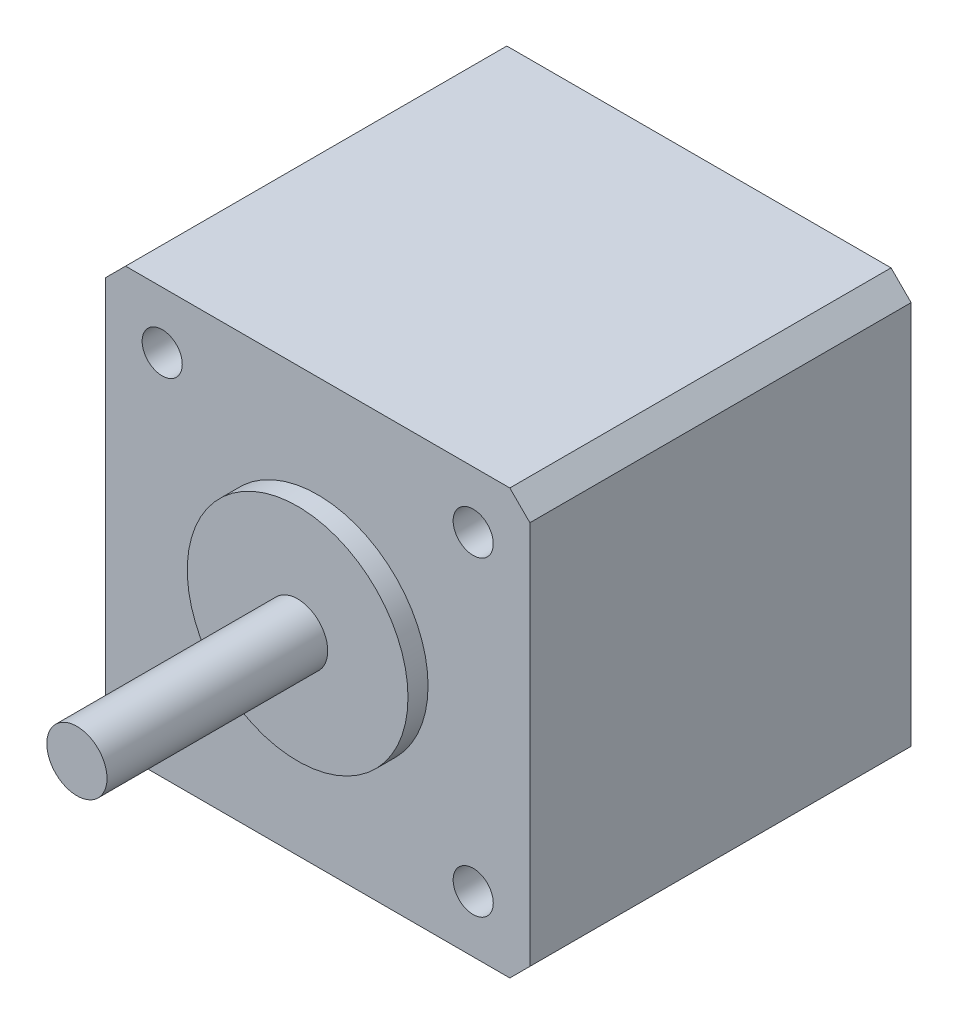
SolidWorks part; units mm, degrees
ref_plane "Plan de face" through (0, 0, 0) normal (0, 0, 1) x (1, 0, 0)
ref_plane "Plan de dessus" through (0, 0, 0) normal (0, 1, 0) x (1, 0, 0)
ref_plane "Plan de droite" through (0, 0, 0) normal (1, 0, 0) x (0, 0, -1)
sketch "Esquisse1" plane through (0, 0, 0) normal (0, 0, 1) x (1, 0, 0)
  line L0 (0, 21.15) -> (0, -21.15) construction
  line L1 (-19.15, -21.15) -> (19.15, -21.15)
  line L2 (-21.15, -19.15) -> (-21.15, 19.15)
  line L3 (-19.15, 21.15) -> (19.15, 21.15)
  line L4 (21.15, -19.15) -> (21.15, 19.15)
  line L5 (-21.15, -21.15) -> (21.15, 21.15) construction
  line L6 (-21.15, 21.15) -> (21.15, -21.15) construction
  line L7 (0, 0) -> (-21.15, 0) construction
  line L8 (-21.15, 19.15) -> (-19.15, 21.15)
  line L9 (21.15, 19.15) -> (19.15, 21.15)
  line L10 (19.15, -21.15) -> (21.15, -19.15)
  line L11 (-19.15, -21.15) -> (-21.15, -19.15)
  circle A0 centre (-15.5, 15.5) radius 2
  circle A1 centre (15.5, 15.5) radius 2
  circle A2 centre (15.5, -15.5) radius 2
  circle A3 centre (-15.5, -15.5) radius 2
  point P0 (0, 0)
  point P12 (15.5, 15.5)
  dimension "D4" = 4
  dimension "D1" = 42.3
  dimension "D2" = 42.3
  dimension "D3" = 15.5
extrude "BASE RECTANGULAIRE" add sketch "Esquisse1" along normal blind 38
sketch "Esquisse2" plane through (0, 0, 38) normal (0, 0, 1) x (1, 0, 0)
  circle A0 centre (0, 0) radius 11
  dimension "D1" = 22
extrude "BOSS DISQUE" add sketch "Esquisse2" along normal blind 2
sketch "Esquisse3" plane through (0, 0, 40) normal (0, 0, 1) x (1, 0, 0)
  circle A0 centre (0, 0) radius 3
  dimension "D1" = 6
extrude "BOSS AXE" add sketch "Esquisse3" along normal blind 22
